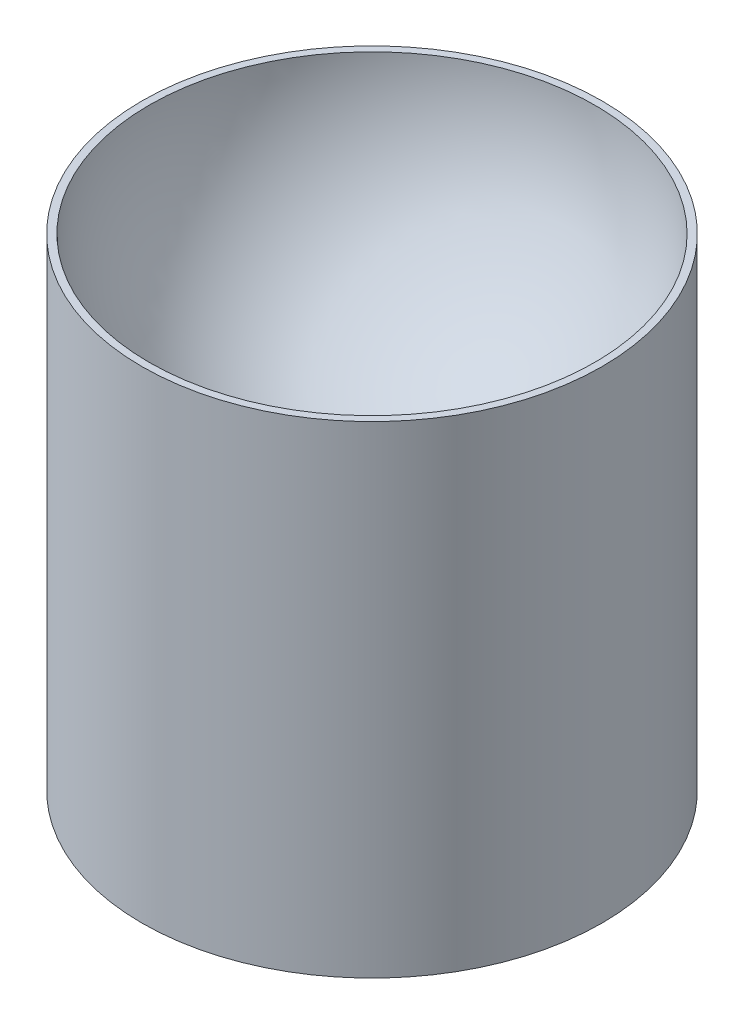
SolidWorks part; units mm, degrees
ref_plane "Front Plane" through (0, 0, 0) normal (0, 0, 1) x (1, 0, 0)
ref_plane "Top Plane" through (0, 0, 0) normal (0, 1, 0) x (1, 0, 0)
ref_plane "Right Plane" through (0, 0, 0) normal (1, 0, 0) x (0, 0, -1)
sketch "Sketch1" plane through (0, 0, 0) normal (0, 0, 1) x (1, 0, 0)
  line L0 (-31.685, 33.185) -> (-31.685, -33.185)
  line L1 (-30.685, 33.185) -> (-31.685, 33.185)
  line L2 (55, 0) -> (-55, 0) construction
  line L3 (-30.685, -33.185) -> (-31.685, -33.185)
  line L4 (0, 2.5) -> (0, -2.5)
  arc A0 (-30.685, 33.185) -> (0, 2.5) centre (0, 33.185) ccw
  arc A1 (-30.685, -33.185) -> (0, -2.5) centre (0, -33.185) cw
  point P1 (-26.8746, 44.8683)
  dimension "D1" = 31.685
  dimension "D2" = 1
  dimension "D3" = 5
revolve "Revolve1" add sketch "Sketch1" angle 360 about L4
